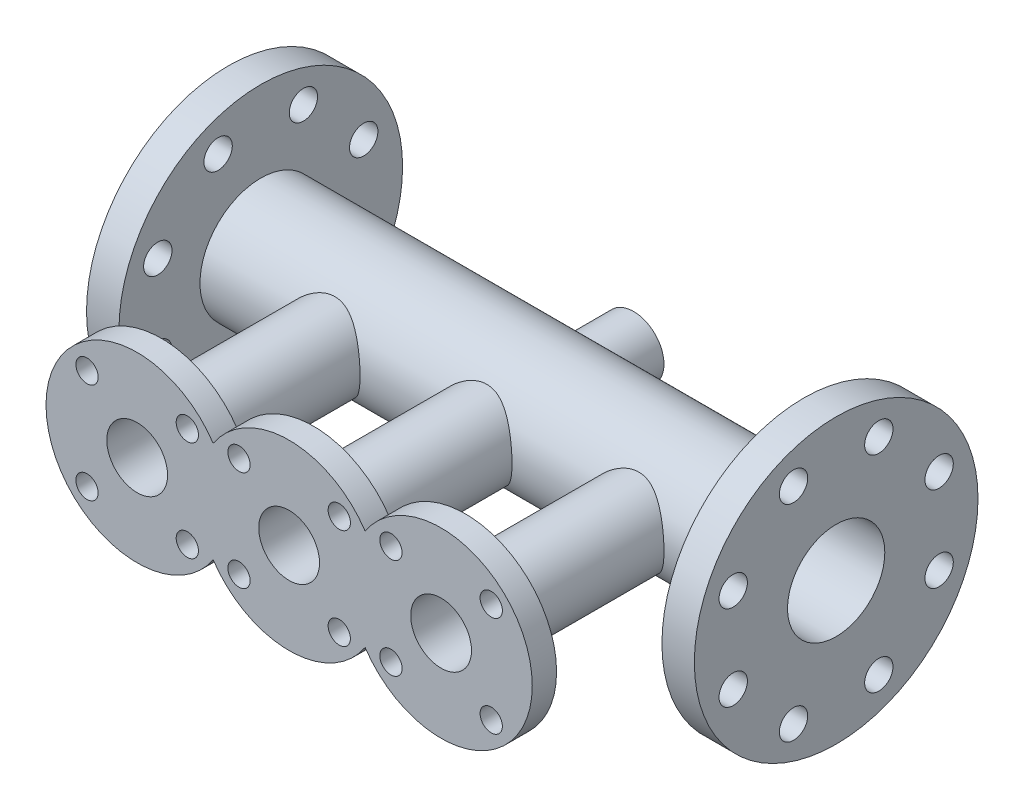
SolidWorks part; units mm, degrees
ref_plane "前视基准面" through (0, 0, 0) normal (0, 0, 1) x (1, 0, 0)
ref_plane "上视基准面" through (0, 0, 0) normal (0, 1, 0) x (1, 0, 0)
ref_plane "右视基准面" through (0, 0, 0) normal (1, 0, 0) x (0, 0, -1)
sketch "草图1" plane through (0, 0, 0) normal (1, 0, 0) x (0, 0, -1)
  circle A0 centre (0, 0) radius 30
extrude "凸台-拉伸1" add sketch "草图1" along normal blind 300
sketch "草图2" plane through (0, 0, 0) normal (1, 0, 0) x (0, 0, -1)
  circle A0 centre (0, 0) radius 70
extrude "凸台-拉伸2" add sketch "草图2" along normal blind 16
ref_plane "基准面1" through (284, 0, 0) normal (1, 0, 0) x (0, 0, -1)
sketch "草图3" plane through (284, 0, 0) normal (1, 0, 0) x (0, 0, -1)
  circle A0 centre (0, 0) radius 70
extrude "凸台-拉伸3" add sketch "草图3" along normal blind 16
sketch "草图4" plane through (0, 0, 0) normal (0, 0, 1) x (1, 0, 0)
  circle A0 centre (75, 0) radius 20
extrude "凸台-拉伸4" add sketch "草图4" along normal blind 120
sketch "草图5" plane through (0, 0, 0) normal (0, 0, 1) x (1, 0, 0)
  circle A0 centre (150, 0) radius 20
extrude "凸台-拉伸5" add sketch "草图5" along normal blind 120
sketch "草图6" plane through (0, 0, 0) normal (0, 0, 1) x (1, 0, 0)
  circle A0 centre (225, 0) radius 20
extrude "凸台-拉伸6" add sketch "草图6" along normal blind 120
ref_plane "基准面2" through (0, 0, -50) normal (0, 0, 1) x (1, 0, 0)
sketch "草图7" plane through (0, 0, -50) normal (0, 0, 1) x (1, 0, 0)
  circle A0 centre (150, 0) radius 15
extrude "凸台-拉伸7" add sketch "草图7" along normal blind 50
ref_plane "基准面3" through (0, 0, 108) normal (0, 0, 1) x (1, 0, 0)
sketch "草图8" plane through (0, 0, 108) normal (0, 0, 1) x (1, 0, 0)
  circle A0 centre (75, 0) radius 45
extrude "凸台-拉伸8" add sketch "草图8" along normal blind 12
sketch "草图9" plane through (0, 0, 108) normal (0, 0, 1) x (1, 0, 0)
  circle A0 centre (150, 0) radius 45
extrude "凸台-拉伸9" add sketch "草图9" along normal blind 12
sketch "草图10" plane through (0, 0, 108) normal (0, 0, 1) x (1, 0, 0)
  circle A0 centre (225, 0) radius 45
extrude "凸台-拉伸10" add sketch "草图10" along normal blind 12
sketch "草图11" plane through (0, 0, 0) normal (1, 0, 0) x (0, 0, -1)
  circle A0 centre (0, 0) radius 24
extrude "切除-拉伸1" cut sketch "草图11" along normal through all
ref_plane "基准面4" through (0, 0, 120) normal (0, 0, 1) x (1, 0, 0)
sketch "草图12" plane through (0, 0, 120) normal (0, 0, 1) x (1, 0, 0)
  circle A0 centre (75, 0) radius 15
extrude "切除-拉伸2" cut sketch "草图12" against normal blind 120
sketch "草图13" plane through (0, 0, 120) normal (0, 0, 1) x (1, 0, 0)
  circle A0 centre (150, 0) radius 15
extrude "切除-拉伸3" cut sketch "草图13" against normal blind 120
sketch "草图14" plane through (0, 0, 120) normal (0, 0, 1) x (1, 0, 0)
  circle A0 centre (225, 0) radius 15
extrude "切除-拉伸4" cut sketch "草图14" against normal blind 120
sketch "草图15" plane through (0, 0, -50) normal (0, 0, 1) x (1, 0, 0)
  circle A0 centre (150, 0) radius 6
extrude "切除-拉伸5" cut sketch "草图15" along normal blind 50
sketch "草图18" plane through (0, 0, 120) normal (0, 0, 1) x (1, 0, 0)
  circle A0 centre (99.7487, 24.7487) radius 5.5
  circle A1 centre (50.2513, 24.7487) radius 5.5
  circle A2 centre (50.2513, -24.7487) radius 5.5
  circle A3 centre (99.7487, -24.7487) radius 5.5
extrude "切除-拉伸9" cut sketch "草图18" against normal blind 12
sketch "草图19" plane through (0, 0, 120) normal (0, 0, 1) x (1, 0, 0)
  circle A0 centre (174.7487, 24.7487) radius 5.5
  circle A1 centre (125.2513, 24.7487) radius 5.5
  circle A2 centre (125.2513, -24.7487) radius 5.5
  circle A3 centre (174.7487, -24.7487) radius 5.5
extrude "切除-拉伸10" cut sketch "草图19" against normal blind 12
sketch "草图20" plane through (0, 0, 120) normal (0, 0, 1) x (1, 0, 0)
  circle A0 centre (249.7487, 24.7487) radius 5.5
  circle A1 centre (200.2513, 24.7487) radius 5.5
  circle A2 centre (200.2513, -24.7487) radius 5.5
  circle A3 centre (249.7487, -24.7487) radius 5.5
extrude "切除-拉伸11" cut sketch "草图20" against normal blind 12
sketch "草图21" plane through (0, 0, 0) normal (1, 0, 0) x (0, 0, -1)
  circle A0 centre (-50.8134, 21.0476) radius 7
  circle A1 centre (-21.0476, 50.8134) radius 7
  circle A2 centre (21.0476, 50.8134) radius 7
  circle A3 centre (50.8134, 21.0476) radius 7
  circle A4 centre (50.8134, -21.0476) radius 7
  circle A5 centre (21.0476, -50.8134) radius 7
  circle A6 centre (-21.0476, -50.8134) radius 7
  circle A7 centre (-50.8134, -21.0476) radius 7
extrude "切除-拉伸12" cut sketch "草图21" along normal blind 16
sketch "草图22" plane through (284, 0, 0) normal (1, 0, 0) x (0, 0, -1)
  circle A0 centre (-50.8134, 21.0476) radius 7
  circle A1 centre (-21.0476, 50.8134) radius 7
  circle A2 centre (21.0476, 50.8134) radius 7
  circle A3 centre (50.8134, 21.0476) radius 7
  circle A4 centre (50.8134, -21.0476) radius 7
  circle A5 centre (21.0476, -50.8134) radius 7
  circle A6 centre (-21.0476, -50.8134) radius 7
  circle A7 centre (-50.8134, -21.0476) radius 7
extrude "切除-拉伸13" cut sketch "草图22" along normal blind 16
